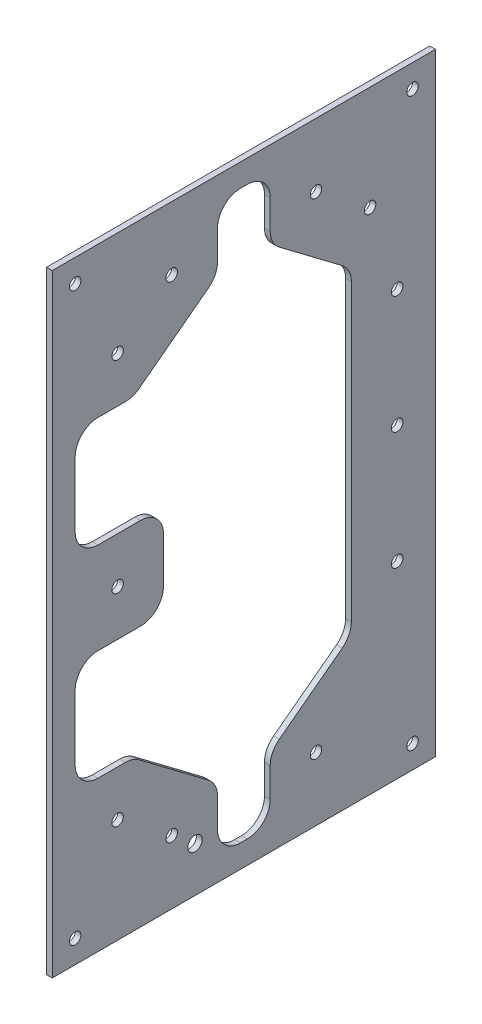
SolidWorks part; units mm, degrees
material "6061-T6 (SS)"
ref_plane "Front Plane" through (0, 0, 0) normal (0, 0, 1) x (1, 0, 0)
ref_plane "Top Plane" through (0, 0, 0) normal (0, 1, 0) x (1, 0, 0)
ref_plane "Right Plane" through (0, 0, 0) normal (1, 0, 0) x (0, 0, -1)
sketch "Sketch1" plane through (0, 0, 0) normal (1, 0, 0) x (0, 0, -1)
  line L0 (0, -169.8625) -> (212.5, -169.8625) construction
  line L1 (0, 0) -> (212.5, 0)
  line L2 (0, 0) -> (0, -339.725)
  line L3 (0, -339.725) -> (212.5, -339.725)
  line L4 (212.5, 0) -> (212.5, -339.725)
  line L5 (153.5, -35.2425) -> (59, -35.2425) construction
  line L6 (191.25, -104.5325) -> (191.25, -169.8625) construction
  line L7 (13.5, -50.2425) -> (59, -50.2425) construction
  line L8 (36.25, -50.2425) -> (36.25, -169.8625) construction
  line L9 (106.25, 0) -> (106.25, -339.725) construction
  line L10 (173.5, -104.5325) -> (191.25, -104.5325) construction
  circle A0 centre (12.7, -12.7) radius 3.175
  circle A1 centre (199.8, -12.7) radius 3.175
  circle A2 centre (66.25, -35.2425) radius 3.175
  circle A3 centre (146.25, -35.2425) radius 3.175
  circle A4 centre (176.25, -57.8625) radius 3.175
  circle A5 centre (36.25, -57.8625) radius 3.175
  circle A6 centre (191.25, -104.5325) radius 3.175
  circle A7 centre (36.25, -169.8625) radius 3.175
  circle A8 centre (191.25, -169.8625) radius 3.175
  circle A9 centre (36.25, -281.8625) radius 3.175
  circle A10 centre (66.25, -304.4825) radius 3.175
  circle A11 centre (12.7, -327.025) radius 3.175
  circle A12 centre (199.8, -327.025) radius 3.175
  circle A13 centre (146.25, -304.4825) radius 3.175
  circle A14 centre (191.25, -235.1925) radius 3.175
  dimension "D1" = 339.725
  dimension "D2" = 212.5
  dimension "D3" = 40
  dimension "D4" = 112
  dimension "D5" = 85
  dimension "D6" = 157.1625
extrude "Boss-Extrude1" add sketch "Sketch1" along normal blind 3.175
sketch "Sketch2" plane through (3.175, 0, 0) normal (1, 0, 0) x (0, 0, -1)
  line L1 (165.85, -88.1617) -> (165.85, -251.5633)
  line L4 (0, 0) -> (0, -339.725)
  line L5 (0, -339.725) -> (212.5, -339.725)
  line L6 (212.5, -339.725) -> (212.5, 0)
  line L7 (212.5, 0) -> (0, 0)
  line L8 (0, 0) -> (0, -339.725)
  line L9 (0, -339.725) -> (212.5, -339.725)
  line L10 (212.5, -339.725) -> (212.5, 0)
  line L11 (212.5, 0) -> (0, 0)
  line L14 (25.4, -144.4625) -> (48.95, -144.4625)
  line L15 (25.4, -83.2625) -> (40.5014, -83.2625)
  line L16 (12.7, -95.9625) -> (12.7, -131.7625)
  line L17 (34.7163, -60.6425) -> (37.7837, -60.6425)
  line L18 (61.65, -70.5625) -> (61.65, -70.522)
  line L19 (61.65, -182.5625) -> (61.65, -157.1625)
  line L20 (36.25, -57.8625) -> (66.25, -35.2425) construction
  line L21 (48.1473, -80.703) -> (86.5959, -51.7127)
  line L22 (91.65, -25.4) -> (91.65, -41.5722)
  line L23 (120.85, -25.4) -> (120.85, -41.5722)
  line L24 (104.35, -12.7) -> (108.15, -12.7)
  line L25 (176.25, -57.8625) -> (146.25, -35.2425) construction
  line L26 (125.9041, -51.7127) -> (160.7959, -78.0212)
  line L27 (0, -169.8625) -> (212.5, -169.8625) construction
  line L28 (176.25, -281.8625) -> (146.25, -304.4825) construction
  line L29 (36.25, -281.8625) -> (66.25, -304.4825) construction
  line L30 (125.9041, -288.0123) -> (160.7959, -261.7038)
  line L31 (104.35, -327.025) -> (108.15, -327.025)
  line L32 (120.85, -314.325) -> (120.85, -298.1528)
  line L33 (91.65, -314.325) -> (91.65, -298.1528)
  line L34 (48.1473, -259.022) -> (86.5959, -288.0123)
  line L35 (61.65, -269.1625) -> (61.65, -269.203)
  line L36 (34.7163, -279.0825) -> (37.7837, -279.0825)
  line L37 (12.7, -243.7625) -> (12.7, -207.9625)
  line L38 (25.4, -256.4625) -> (40.5014, -256.4625)
  line L39 (25.4, -195.2625) -> (48.95, -195.2625)
  circle A0 centre (176.25, -57.8625) radius 3.175 construction
  circle A1 centre (146.25, -35.2425) radius 3.175 construction
  circle A2 centre (66.25, -35.2425) radius 3.175 construction
  circle A3 centre (36.25, -57.8625) radius 3.175 construction
  circle A4 centre (36.25, -169.8625) radius 3.175 construction
  circle A5 centre (36.25, -281.8625) radius 3.175 construction
  circle A6 centre (66.25, -304.4825) radius 3.175 construction
  circle A7 centre (146.25, -304.4825) radius 3.175 construction
  circle A8 centre (191.25, -235.1925) radius 3.175 construction
  circle A9 centre (191.25, -169.8625) radius 3.175 construction
  circle A10 centre (191.25, -104.5325) radius 3.175 construction
  circle A11 centre (176.25, -57.8625) radius 3.175 construction
  circle A12 centre (146.25, -35.2425) radius 3.175 construction
  circle A13 centre (66.25, -35.2425) radius 3.175 construction
  circle A14 centre (36.25, -57.8625) radius 3.175 construction
  circle A15 centre (36.25, -169.8625) radius 3.175 construction
  circle A16 centre (36.25, -281.8625) radius 3.175 construction
  circle A17 centre (66.25, -304.4825) radius 3.175 construction
  circle A18 centre (146.25, -304.4825) radius 3.175 construction
  circle A19 centre (191.25, -235.1925) radius 3.175 construction
  circle A20 centre (191.25, -169.8625) radius 3.175 construction
  circle A21 centre (191.25, -104.5325) radius 3.175 construction
  arc A28 (48.95, -144.4625) -> (61.65, -157.1625) centre (48.95, -157.1625) cw
  arc A29 (12.7, -131.7625) -> (25.4, -144.4625) centre (25.4, -131.7625) ccw
  arc A30 (12.7, -95.9625) -> (25.4, -83.2625) centre (25.4, -95.9625) cw
  arc A33 (165.85, -88.1617) -> (160.7959, -78.0212) centre (153.15, -88.1617) ccw
  arc A34 (125.9041, -51.7127) -> (120.85, -41.5722) centre (133.55, -41.5722) cw
  arc A35 (108.15, -12.7) -> (120.85, -25.4) centre (108.15, -25.4) cw
  arc A36 (104.35, -12.7) -> (91.65, -25.4) centre (104.35, -25.4) ccw
  arc A37 (86.5959, -51.7127) -> (91.65, -41.5722) centre (78.95, -41.5722) ccw
  arc A38 (48.1473, -80.703) -> (40.5014, -83.2625) centre (40.5014, -70.5625) cw
  circle A39 centre (36.25, -281.8625) radius 3.175 construction
  circle A40 centre (66.25, -304.4825) radius 3.175 construction
  circle A41 centre (146.25, -304.4825) radius 3.175 construction
  circle A42 centre (176.25, -281.8625) radius 3.175 construction
  arc A43 (48.1473, -259.022) -> (40.5014, -256.4625) centre (40.5014, -269.1625) ccw
  arc A44 (86.5959, -288.0123) -> (91.65, -298.1528) centre (78.95, -298.1528) cw
  arc A45 (104.35, -327.025) -> (91.65, -314.325) centre (104.35, -314.325) cw
  arc A46 (108.15, -327.025) -> (120.85, -314.325) centre (108.15, -314.325) ccw
  arc A47 (125.9041, -288.0123) -> (120.85, -298.1528) centre (133.55, -298.1528) ccw
  arc A48 (165.85, -251.5633) -> (160.7959, -261.7038) centre (153.15, -251.5633) cw
  arc A49 (12.7, -243.7625) -> (25.4, -256.4625) centre (25.4, -243.7625) ccw
  arc A50 (12.7, -207.9625) -> (25.4, -195.2625) centre (25.4, -207.9625) cw
  arc A51 (48.95, -195.2625) -> (61.65, -182.5625) centre (48.95, -182.5625) ccw
  point P73 (61.65, -83.2625)
  point P78 (61.65, -60.6425)
  point P92 (61.65, -279.0825)
  point P110 (61.65, -169.8625)
  point P114 (165.85, -169.8625)
  point P115 (61.65, -256.4625)
  dimension "D11" = 25.4
  dimension "D13" = 25.4
  dimension "D17" = 12.7
  dimension "D2" = 25.4
  dimension "D7" = 25.4
  dimension "D8" = 25.4
  dimension "D9" = 25.4
  dimension "D14" = 25.4
  dimension "D15" = 12.7
  dimension "D16" = 25.4
  dimension "D1" = 0
extrude "Cut-Extrude1" cut sketch "Sketch2" against normal through all
sketch "Sketch3" plane through (0, 0, 0) normal (-1, 0, 0) x (0, 0, 1)
  line L0 (-212.5, -339.725) -> (-79.15, -339.725)
  line L1 (0, -339.725) -> (-212.5, -339.725) construction
  line L2 (-79.15, -339.725) -> (-79.15, -314.725)
  line L3 (-212.5, 0) -> (-83.8431, 0)
  line L4 (-212.5, 0) -> (0, 0) construction
  circle A0 centre (-79.15, -314.725) radius 4
  dimension "D4" = 8
  dimension "D1" = 133.35
  dimension "D2" = 25
  dimension "D3" = 128.6569
extrude "Cut-Extrude2" cut sketch "Sketch3" against normal blind 13.97
